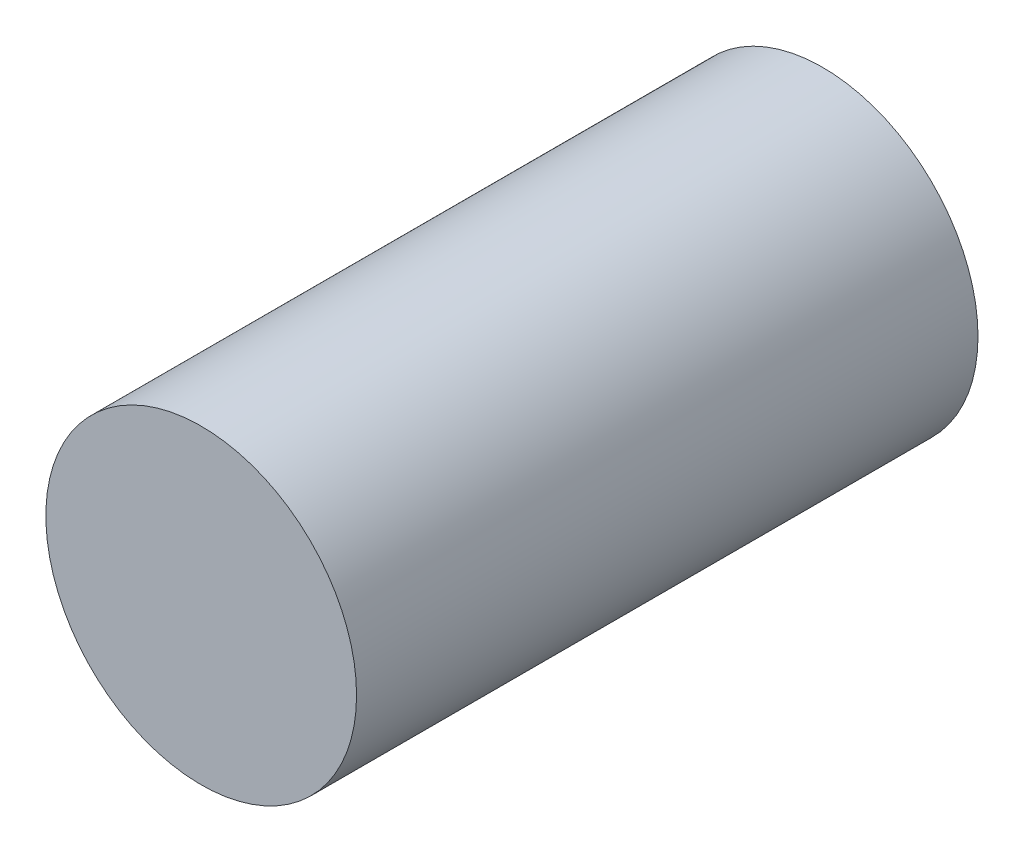
SolidWorks part; units mm, degrees
ref_plane "Ön Düzlem" through (0, 0, 0) normal (0, 0, 1) x (1, 0, 0)
ref_plane "Üst Düzlem" through (0, 0, 0) normal (0, 1, 0) x (1, 0, 0)
ref_plane "Sağ Düzlem" through (0, 0, 0) normal (1, 0, 0) x (0, 0, -1)
sketch "Sketch1" plane through (0, 0, 0) normal (0, 0, 1) x (1, 0, 0)
  circle A0 centre (-66.5473, -10.9242) radius 25
extrude "Boss-Extrude1" add sketch "Sketch1" along normal blind 100
